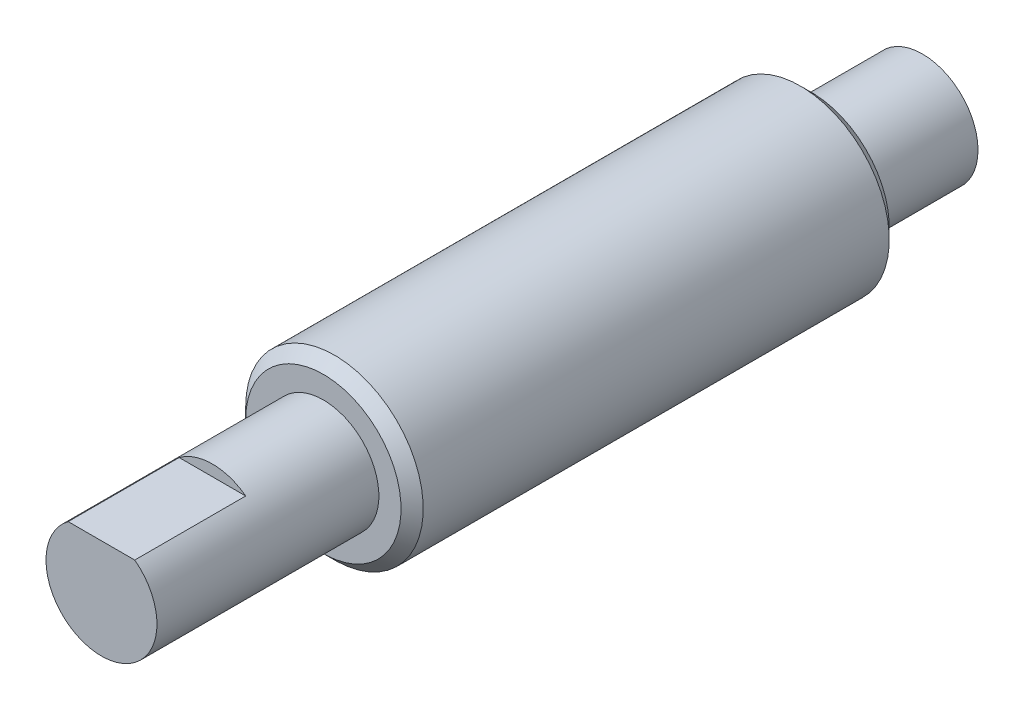
SolidWorks part; units mm, degrees
material "AISI 1020"
ref_plane "Front Plane" through (0, 0, 0) normal (0, 0, 1) x (1, 0, 0)
ref_plane "Top Plane" through (0, 0, 0) normal (0, 1, 0) x (1, 0, 0)
ref_plane "Right Plane" through (0, 0, 0) normal (1, 0, 0) x (0, 0, -1)
sketch "Sketch1" plane through (0, 0, 0) normal (0, 1, 0) x (1, 0, 0)
  line L0 (0, 74) -> (0, 0)
  line L1 (0, 0) -> (5, 0)
  line L2 (5, 0) -> (5, 20)
  line L3 (5, 20) -> (7, 20)
  line L4 (8, 21) -> (8, 63)
  line L5 (7, 64) -> (5, 64)
  line L6 (5, 64) -> (5, 74)
  line L8 (8, 63) -> (7, 64)
  line L9 (7, 20) -> (8, 21)
  line L10 (0, 74) -> (0, 76.8868)
  line L11 (0, 76.8868) -> (5, 74)
  point P6 (8, 20)
  point P7 (8, 64)
  dimension "D1" = 74
  dimension "D2" = 20
  dimension "D3" = 10
  dimension "D4" = 5
  dimension "D5" = 5
  dimension "D6" = 8
  dimension "D7" = 60
  dimension "D8" = 2.8868
revolve "Revolve1" add sketch "Sketch1" angle 360 about L0
sketch "Sketch2" plane through (0, 0, 0) normal (0, 0, 1) x (1, 0, 0)
  line L0 (-3, 4) -> (3, 4)
  circle A0 centre (0, 0) radius 5 construction
  circle A1 centre (0, 0) radius 5 construction
  arc A2 (3, 4) -> (-3, 4) centre (0, 0) ccw
  dimension "D1" = 4
extrude "Cut-Extrude1" cut sketch "Sketch2" against normal blind 10
